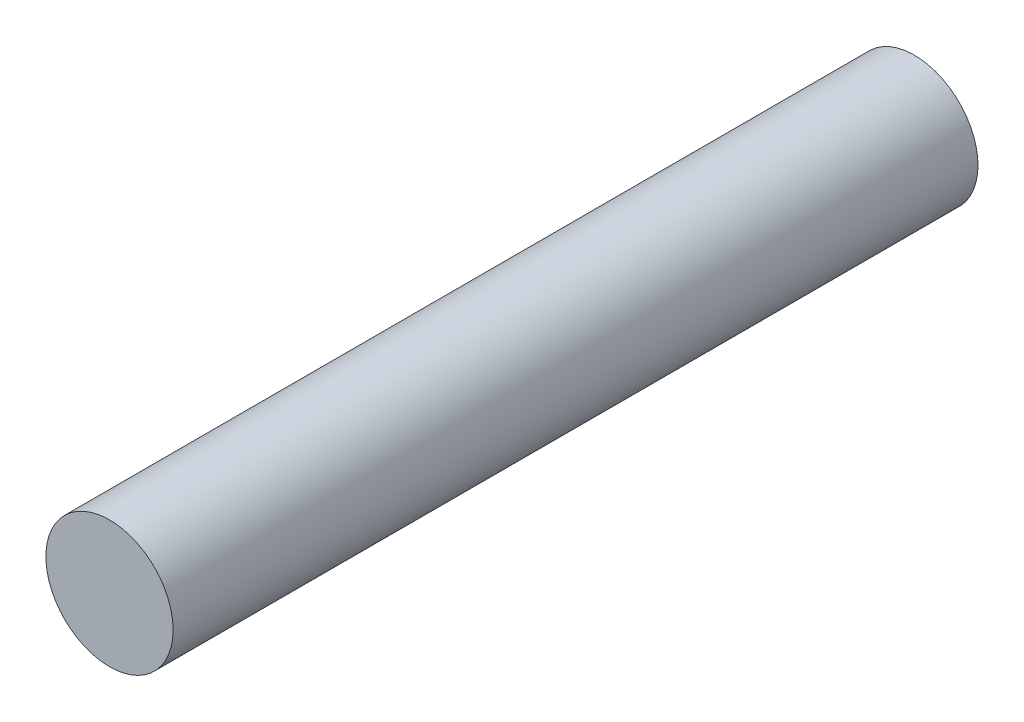
SolidWorks part; units mm, degrees
ref_plane "前视基准面" through (0, 0, 0) normal (0, 0, 1) x (1, 0, 0)
ref_plane "上视基准面" through (0, 0, 0) normal (0, 1, 0) x (1, 0, 0)
ref_plane "右视基准面" through (0, 0, 0) normal (1, 0, 0) x (0, 0, -1)
sketch "草图1" plane through (0, 0, 0) normal (0, 0, 1) x (1, 0, 0)
  circle A0 centre (0, 0) radius 2.45
  dimension "D1" = 4.9
extrude "凸台-拉伸1" add sketch "草图1" along normal blind 31
